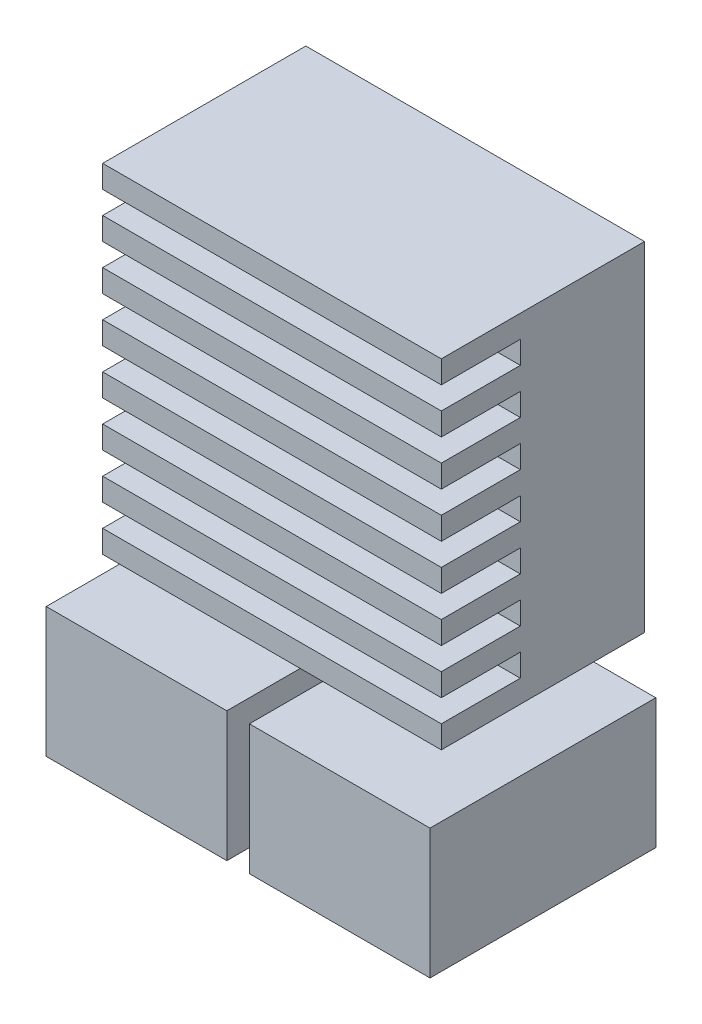
SolidWorks part; units mm, degrees
ref_plane "Přední rovina" through (0, 0, 0) normal (0, 0, 1) x (1, 0, 0)
ref_plane "Horní rovina" through (0, 0, 0) normal (0, 1, 0) x (1, 0, 0)
ref_plane "Pravá rovina" through (0, 0, 0) normal (1, 0, 0) x (0, 0, -1)
sketch "Skica1" plane through (0, 0, 0) normal (0, 0, 1) x (1, 0, 0)
  line L1 (15, 15) -> (-15, 15)
  line L2 (15, 15) -> (15, -15)
  line L3 (15, -15) -> (-15, -15)
  line L4 (-15, 15) -> (-15, -15)
  line L5 (15, 15) -> (-15, -15) construction
  line L6 (15, -15) -> (-15, 15) construction
  circle A0 centre (5, 5) radius 1.5
  circle A1 centre (-5, 5) radius 1.5
  circle A2 centre (0, -5) radius 1.5
  point P0 (0, 0)
  point P12 (0, 0)
  point P13 (0, 0)
  point P14 (0, 0)
  dimension "D6" = 3
  dimension "D1" = 30
  dimension "D2" = 30
  dimension "D3" = 10
  dimension "D4" = 10
  dimension "D5" = 10
extrude "Přidat vysunutím1" add sketch "Skica1" along normal blind 7
sketch "Skica2" plane through (0, 0, 7) normal (0, 0, 1) x (1, 0, 0)
  line L4 (-15, 15) -> (-15, -15)
  line L5 (-15, -15) -> (15, -15)
  line L6 (15, -15) -> (15, 15)
  line L7 (15, 15) -> (-15, 15)
  line L8 (-15, 15) -> (-15, -15)
  line L9 (-15, -15) -> (15, -15)
  line L10 (15, -15) -> (15, 15)
  line L11 (15, 15) -> (-15, 15)
  dimension "D1" = 0
extrude "Přidat vysunutím2" add sketch "Skica2" along normal blind 11
sketch "Skica3" plane through (15, 0, 0) normal (1, 0, 0) x (0, 0, -1)
  line L0 (-18, -15) -> (-18, 15) construction
  line L1 (-18, 13) -> (-11, 13)
  line L2 (-18, 13) -> (-18, 11)
  line L3 (-18, 11) -> (-11, 11)
  line L4 (-11, 13) -> (-11, 11)
  line L5 (-18, 15) -> (0, 15) construction
  line L6 (-18, 7) -> (-11, 7)
  line L7 (-11, 9) -> (-11, 7)
  line L8 (-18, 9) -> (-11, 9)
  line L9 (-18, 9) -> (-18, 7)
  line L10 (-18, 3) -> (-11, 3)
  line L11 (-11, 5) -> (-11, 3)
  line L12 (-18, 5) -> (-11, 5)
  line L13 (-18, 5) -> (-18, 3)
  line L14 (-18, -1) -> (-11, -1)
  line L15 (-11, 1) -> (-11, -1)
  line L16 (-18, 1) -> (-11, 1)
  line L17 (-18, 1) -> (-18, -1)
  line L18 (-18, -5) -> (-11, -5)
  line L19 (-11, -3) -> (-11, -5)
  line L20 (-18, -3) -> (-11, -3)
  line L21 (-18, -3) -> (-18, -5)
  line L22 (-18, -9) -> (-11, -9)
  line L23 (-11, -7) -> (-11, -9)
  line L24 (-18, -7) -> (-11, -7)
  line L25 (-18, -7) -> (-18, -9)
  line L26 (-18, -13) -> (-11, -13)
  line L27 (-11, -11) -> (-11, -13)
  line L28 (-18, -11) -> (-11, -11)
  line L29 (-18, -11) -> (-18, -13)
  dimension "D1" = 2
  dimension "D2" = 2
  dimension "D3" = 7
  dimension "D4" = 7
extrude "Odebrat vysunutím1" cut sketch "Skica3" against normal up to surface (30 mm away) up to face at (-15, 0, 9)
sketch "Skica4" plane through (0, -15, 0) normal (0, -1, 0) x (1, 0, 0)
  line L0 (-15, 18) -> (-15, 0) construction
  line L1 (15, 18) -> (15, 0) construction
  line L2 (-15, 0) -> (15, 0) construction
  circle A0 centre (9, 6) radius 1.5
  circle A1 centre (-9, 6) radius 1.5
  point P10 (0, 0)
  dimension "D3" = 3
  dimension "D1" = 6
  dimension "D2" = 6
  dimension "D4" = 6
extrude "Přidat vysunutím3" add sketch "Skica4" along normal blind 3.5
sketch "Skica5" plane through (0, -18.5, 0) normal (0, -1, 0) x (1, 0, 0)
  line L0 (0, 0) -> (0, 27.507) construction
  line L1 (17, 21) -> (1, 21)
  line L2 (17, 21) -> (17, 1)
  line L3 (17, 1) -> (1, 1)
  line L4 (1, 21) -> (1, 1)
  line L5 (17, 21) -> (1, 1) construction
  line L6 (17, 1) -> (1, 21) construction
  line L7 (-17, 1) -> (-1, 1)
  line L8 (-1, 21) -> (-1, 1)
  line L9 (-17, 21) -> (-1, 21)
  line L10 (-17, 21) -> (-17, 1)
  point P0 (9, 11)
  point P8 (9, 6)
  point P9 (0, 0)
  point P11 (9, 6)
  point P12 (0, 0)
  dimension "D1" = 20
  dimension "D2" = 16
  dimension "D3" = 5
extrude "Přidat vysunutím4" add sketch "Skica5" along normal blind 11.5
sketch "Skica6" plane through (0, -30, 0) normal (0, -1, 0) x (1, 0, 0)
  line L0 (-17, 1) -> (-1, 1) construction
  line L1 (0, 0) -> (0, 20.1414) construction
  line L2 (-4.9585, 6) -> (-6.9793, 9.5)
  line L3 (-6.9793, 9.5) -> (-11.0207, 9.5)
  line L4 (-11.0207, 9.5) -> (-13.0415, 6)
  line L5 (-13.0415, 6) -> (-11.0207, 2.5)
  line L6 (-11.0207, 2.5) -> (-6.9793, 2.5)
  line L7 (-6.9793, 2.5) -> (-4.9585, 6)
  line L8 (6.9793, 2.5) -> (4.9585, 6)
  line L9 (11.0207, 2.5) -> (6.9793, 2.5)
  line L10 (13.0415, 6) -> (11.0207, 2.5)
  line L11 (11.0207, 9.5) -> (13.0415, 6)
  line L12 (6.9793, 9.5) -> (11.0207, 9.5)
  line L13 (4.9585, 6) -> (6.9793, 9.5)
  circle A0 centre (-9, 6) radius 3.5 construction
  point P0 (-9, 6)
  point P1 (-9, 1)
  dimension "D1" = 5
  dimension "D2" = 7
extrude "Přidat vysunutím5" add sketch "Skica6" along normal blind 6.5
chamfer "Zkosení1" distance 3 angle 45 12 edges at (5.9689, -36.5, 4.25) (5.9689, -36.5, 7.75) (9, -36.5, 9.5) (12.0311, -36.5, 7.75) (12.0311, -36.5, 4.25) (9, -36.5, 2.5) (-9, -36.5, 2.5) (-12.0311, -36.5, 4.25) (-12.0311, -36.5, 7.75) (-9, -36.5, 9.5) (-5.9689, -36.5, 7.75) (-5.9689, -36.5, 4.25)
